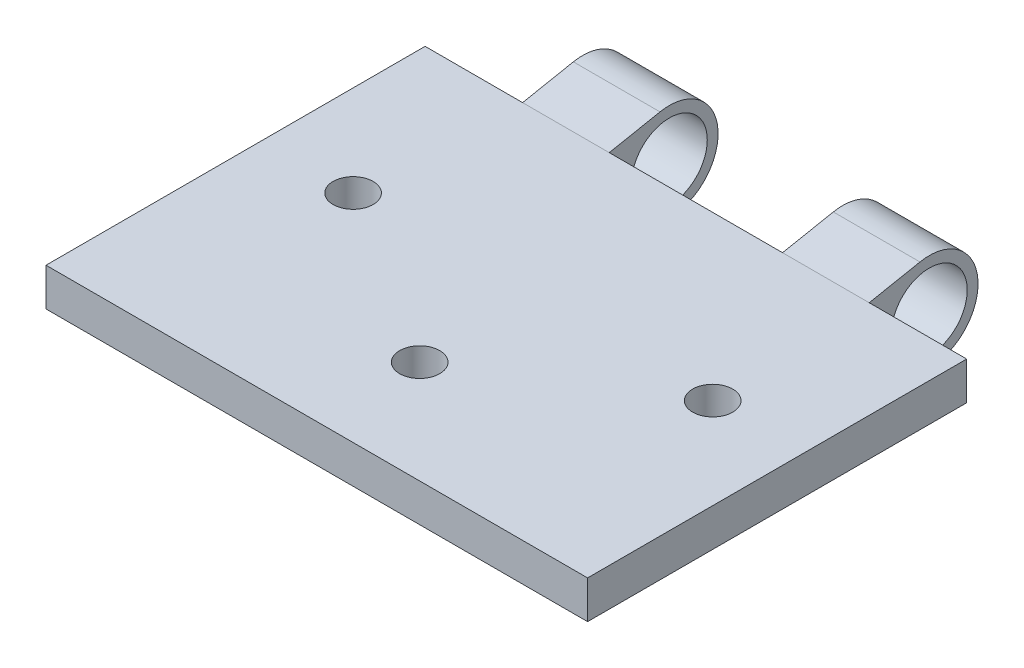
SolidWorks part; units mm, degrees
ref_plane "Front Plane" through (0, 0, 0) normal (0, 0, 1) x (1, 0, 0)
ref_plane "Top Plane" through (0, 0, 0) normal (0, 1, 0) x (1, 0, 0)
ref_plane "Right Plane" through (0, 0, 0) normal (1, 0, 0) x (0, 0, -1)
sketch "Sketch2" plane through (0, 0, 0) normal (0, 1, 0) x (1, 0, 0)
  line L0 (-25, -17.5) -> (-25, 17.5)
  line L1 (-25, 17.5) -> (25, 17.5)
  line L2 (25, 17.5) -> (25, -17.5)
  line L3 (25, -17.5) -> (-25, -17.5)
  line L4 (0, -17.5) -> (0, 17.5) construction
  line L5 (-25, 0) -> (25, 0) construction
  line L6 (0, 0) -> (0, 17.5) construction
  dimension "D1" = 50
  dimension "D2" = 35
extrude "Boss-Extrude1" add sketch "Sketch2" along normal blind 3.5 contours L1 L2 L3 L0
sketch "Sketch3" plane through (0, 3.5, 0) normal (0, 1, 0) x (1, 0, 0)
  line L0 (-25, -17.5) -> (25, -17.5) construction
  line L1 (-25, -17.5) -> (-25, 17.5) construction
  line L2 (25, 17.5) -> (25, -17.5) construction
  line L5 (0, 0) -> (0, 17.5) construction
  line L6 (-25, 17.5) -> (25, 17.5) construction
  circle A0 centre (-16.6, 2.45) radius 1.85
  circle A1 centre (0, -8) radius 1.85
  circle A2 centre (16.6, 2.45) radius 1.85
  point P10 (0, -17.5)
  dimension "D1" = 3.7
  dimension "D2" = 3.7
  dimension "D3" = 3.7
  dimension "D4" = 8.4
  dimension "D5" = 8.4
  dimension "D6" = 8
  dimension "D7" = 2.45
extrude "Cut-Extrude1" cut sketch "Sketch3" against normal through all
ref_plane "Plane1" through (8, 0, 0) normal (1, 0, 0) x (0, 0, -1)
sketch "Sketch5" plane through (8, 0, 0) normal (1, 0, 0) x (0, 0, -1)
  line L0 (17.5, 0) -> (23.05, 0) construction
  line L1 (17.5, 3.5) -> (22.1864, 4.4164)
  line L2 (17.5, 0) -> (19.4014, -2.6339)
  line L3 (17.5, 0) -> (-17.5, 0) construction
  line L4 (17.5, 3.5) -> (17.5, 0)
  arc A0 (19.4014, -2.6339) -> (22.1864, 4.4164) centre (23.05, 0) ccw
  circle A1 centre (23.05, 0) radius 3.5
  point P5 (17.5, 1.75)
  dimension "D1" = 7
  dimension "D2" = 4.5
  dimension "D3" = 5.55
extrude "Boss-Extrude2" add sketch "Sketch5" along normal blind 8
mirror "Mirror1" about plane through (0, 0, 0) normal (1, 0, 0) of "Boss-Extrude2"
